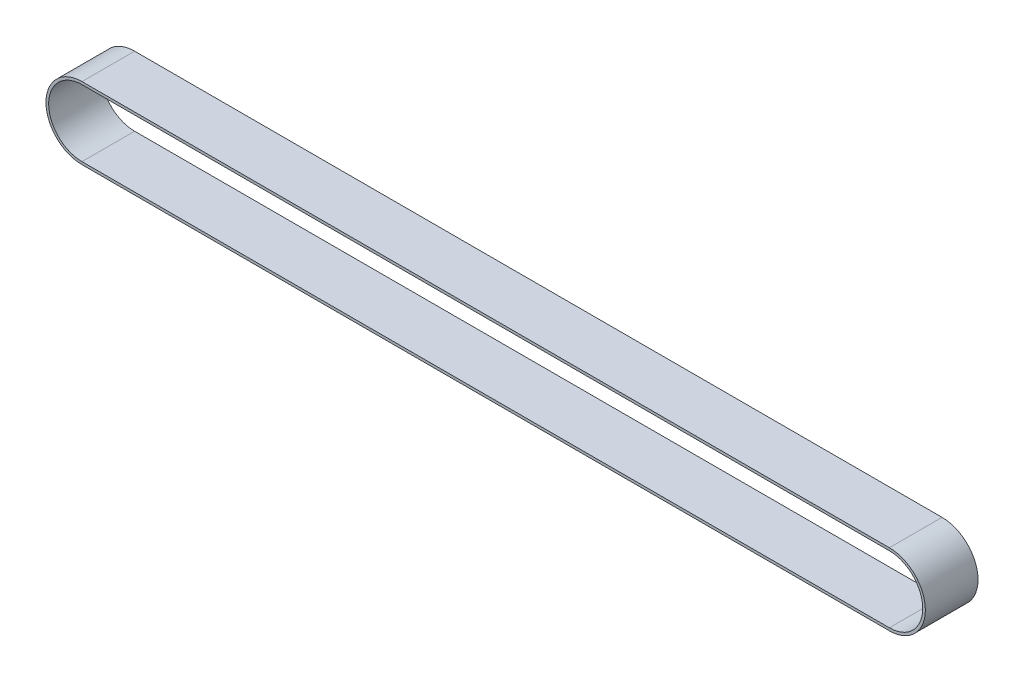
SolidWorks part; units mm, degrees
material "SKD11淬火HRC56-60"
ref_plane "前基準面" through (0, 0, 0) normal (0, 0, 1) x (1, 0, 0)
ref_plane "上基準面" through (0, 0, 0) normal (0, 1, 0) x (1, 0, 0)
ref_plane "右基準面" through (0, 0, 0) normal (1, 0, 0) x (0, 0, -1)
sketch "草图1" plane through (0, 0, 0) normal (0, 0, 1) x (1, 0, 0)
  line L0 (0, 0) -> (460, 0) construction
  line L1 (0, 19) -> (460, 19)
  line L2 (0, -19) -> (460, -19)
  line L3 (0, 20.5) -> (460, 20.5)
  line L4 (0, -20.5) -> (460, -20.5)
  arc A0 (0, 19) -> (0, -19) centre (0, 0) ccw
  arc A1 (460, -19) -> (460, 19) centre (460, 0) ccw
  arc A2 (460, -20.5) -> (460, 20.5) centre (460, 0) ccw
  arc A3 (0, 20.5) -> (0, -20.5) centre (0, 0) ccw
  point P3 (230, 0)
  dimension "D3" = 19
  dimension "D2" = 460
  dimension "D1" = 1.5
extrude "凸台-拉伸1" add sketch "草图1" along normal blind 30
